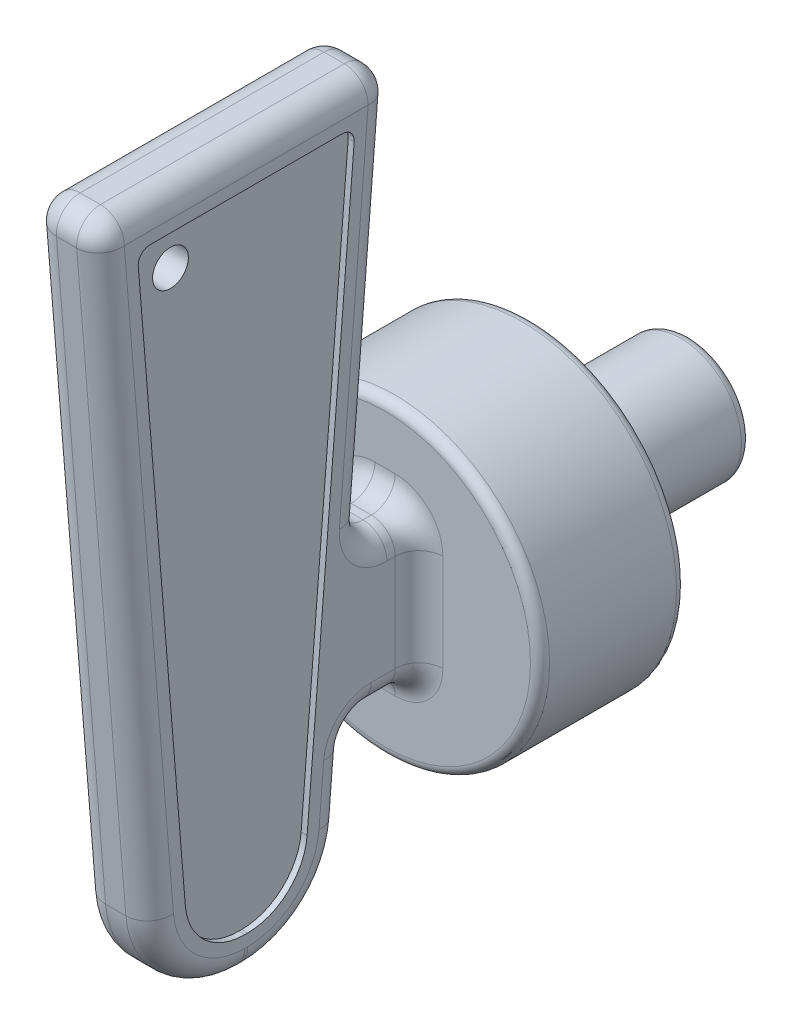
SolidWorks part; units mm, degrees
material "Custom Plastic"
ref_plane "X-Y Datum" through (0, 0, 0) normal (0, 0, 1) x (1, 0, 0)
ref_plane "X-Z Datum" through (0, 0, 0) normal (0, 1, 0) x (1, 0, 0)
ref_plane "Y-Z Datum" through (0, 0, 0) normal (1, 0, 0) x (0, 0, -1)
sketch "Sketch1" plane through (0, 0, 0) normal (0, 0, 1) x (1, 0, 0)
  circle A0 centre (0, 0) radius 13
  dimension "D1" = 26
extrude "Boss-Extrude1" add sketch "Sketch1" along normal blind 12.25
shell "Shell1" thickness 2
sketch "Sketch2" plane through (0, 0, 10.25) normal (0, 0, -1) x (-1, 0, 0)
  circle A1 centre (0, 0) radius 5.1
  dimension "D1" = 10.2
extrude "Boss-Extrude2" add sketch "Sketch2" along normal blind 23.6
sketch "Sketch3" plane through (0, 0, 0) normal (1, 0, 0) x (0, 0, -1)
  line L0 (-12.25, 13) -> (-12.25, -13) construction
  line L1 (-12.25, 13) -> (-12.25, -13)
  line L2 (-12.25, 6.075) -> (-12.25, -6.075)
  line L3 (-26.75, 40) -> (-26.75, -20.1) construction
  line L4 (-12.25, 6.075) -> (-17.1159, 6.075)
  line L5 (-12.25, 6.075) -> (-12.25, -6.075)
  line L6 (-12.25, -6.075) -> (-18.1065, -6.075)
  line L8 (-39.15, 40) -> (-14.35, 40)
  line L9 (-34.25, -20.1) -> (-19.25, -20.1)
  line L10 (-39.15, 40) -> (-34.25, -20.1)
  line L11 (-19.25, -20.1) -> (-14.35, 40)
  line L12 (0, 13) -> (-12.25, 13) construction
  line L13 (0, 13) -> (-12.25, 13)
  point P5 (-12.25, 0)
  point P13 (-26.75, 40)
  point P16 (-26.75, -20.1)
  dimension "D1" = 12.15
  dimension "D2" = 24.8
  dimension "D3" = 15
  dimension "D4" = 60.1
  dimension "D5" = 27
  dimension "D6" = 14.5
extrude "Boss-Extrude3" add sketch "Sketch3" along normal mid plane 5.7 contours L11 L6 L1 L4 | L8 L3 L9 L11 | L3 L8 L10 L9
ref_plane "Plane1" through (0, -5.1, 0) normal (0, -1, 0) x (-1, 0, 0)
sketch "Sketch4" plane through (0, -5.1, 0) normal (0, -1, 0) x (-1, 0, 0)
  line L0 (5.1, 13.35) -> (-5.1, 13.35) construction
  circle A0 centre (0, 4.85) radius 2
  dimension "D1" = 4
  dimension "D2" = 8.5
extrude "Boss-Extrude4" add sketch "Sketch4" along normal blind 4 and the other way up to surface other way up to face at (-5.1, 0, -13.35)
fillet "Fillet1" radius 0.8 1 edges at (0, -9.1, -6.85)
fillet "Fillet2" radius 0.8 3 edges at (-5.1, 0, -13.35) (13, 0, 0) (13, 0, 12.25)
fillet "Fillet3" radius 8 2 edges at (0, -20.1, 34.25) (0, -20.1, 19.25)
fillet "Fillet4" radius 2 2 edges at (0, 40, 39.15) (0, 40, 14.35)
fillet "Fillet5" radius 2 28 edges at (2.85, 12.5437, 36.9115) (-2.85, 12.5437, 36.9115) (2.85, -17.9822, 32.2978) (-2.85, -17.9822, 32.2978) (2.85, 39.3555, 38.4509) (-2.85, 39.3555, 38.4509) (2.85, -20.1, 26.75) (-2.85, -20.1, 26.75) (-2.85, 40, 26.75) (2.85, 40, 26.75) (2.85, -17.9822, 21.2022) (-2.85, -17.9822, 21.2022) (2.85, 39.3555, 15.0491) (-2.85, 39.3555, 15.0491) (2.85, -9.4125, 18.3786) (-2.85, -9.4125, 18.3786) (-2.85, 0, 12.25) (2.85, 0, 12.25) (2.85, 21.9562, 15.8211) (-2.85, 21.9562, 15.8211) (0, -6.075, 18.1065) (-2.85, -6.075, 15.1783) (2.85, -6.075, 15.1783) (0, -6.075, 12.25) (0, 6.075, 12.25) (-2.85, 6.075, 14.683) (2.85, 6.075, 14.683) (0, 6.075, 17.1159)
sketch "Sketch5" plane through (2.85, 0, 0) normal (1, 0, 0) x (0, 0, -1)
  line L8 (-19.9297, 8.4813) -> (-21.2464, -7.6687)
  line L16 (-21.6408, -12.5063) -> (-21.2464, -7.6687)
  line L17 (-16.263, -3.075) -> (-15.25, -3.075)
  line L18 (-15.25, -3.075) -> (-15.25, 3.0842)
  line L19 (-19.9297, 8.4813) -> (-17.6045, 37)
  line L20 (-17.6045, 37) -> (-35.8955, 37)
  line L21 (-35.8955, 37) -> (-31.8592, -12.5063)
  line L22 (-26.8757, -17.1) -> (-26.6243, -17.1)
  line L23 (-21.6408, -12.5063) -> (-21.2464, -7.6687)
  line L24 (-16.263, -3.075) -> (-15.25, -3.075)
  line L25 (-15.25, -3.075) -> (-15.25, 3.0842)
  line L26 (-19.9297, 8.4813) -> (-17.6045, 37)
  line L27 (-17.6045, 37) -> (-35.8955, 37)
  line L28 (-35.8955, 37) -> (-31.8592, -12.5063)
  line L29 (-26.8757, -17.1) -> (-26.6243, -17.1)
  arc A8 (-26.6243, -17.1) -> (-21.6408, -12.5063) centre (-26.6243, -12.1) ccw
  arc A9 (-16.263, -3.075) -> (-21.2464, -7.6687) centre (-16.263, -8.075) ccw
  arc A10 (-19.9297, 8.4813) -> (-15.25, 3.0842) centre (-14.9462, 8.075) ccw
  arc A11 (-31.8592, -12.5063) -> (-26.8757, -17.1) centre (-26.8757, -12.1) ccw
  arc A12 (-26.6243, -17.1) -> (-21.6408, -12.5063) centre (-26.6243, -12.1) ccw
  arc A13 (-16.263, -3.075) -> (-21.2464, -7.6687) centre (-16.263, -8.075) ccw
  arc A14 (-19.9297, 8.4813) -> (-15.25, 3.0842) centre (-14.9462, 8.075) ccw
  arc A15 (-31.8592, -12.5063) -> (-26.8757, -17.1) centre (-26.8757, -12.1) ccw
  dimension "D1" = 1
extrude "Cut-Extrude1" cut sketch "Sketch5" against normal blind 0.5 contours L28 A15 L29 A12 L23 L8 L26 L27
fillet "Fillet6" radius 1 2 edges at (2.6, 37, 17.6045) (2.6, 37, 35.8955)
mirror "Mirror1" about plane through (0, 0, 0) normal (1, 0, 0) of "Fillet6", "Cut-Extrude1"
sketch "Sketch6" plane through (2.35, 0, 0) normal (1, 0, 0) x (0, 0, -1)
  line L0 (-35.5459, 36.6778) -> (-32.6048, 33.9667)
  circle A0 centre (-32.6048, 33.9667) radius 1.5
  arc A3 (-34.8106, 37) -> (-35.8073, 35.9187) centre (-34.8106, 36) ccw construction
  dimension "D2" = 3
  dimension "D1" = 4
extrude "Cut-Extrude2" cut sketch "Sketch6" against normal through all
